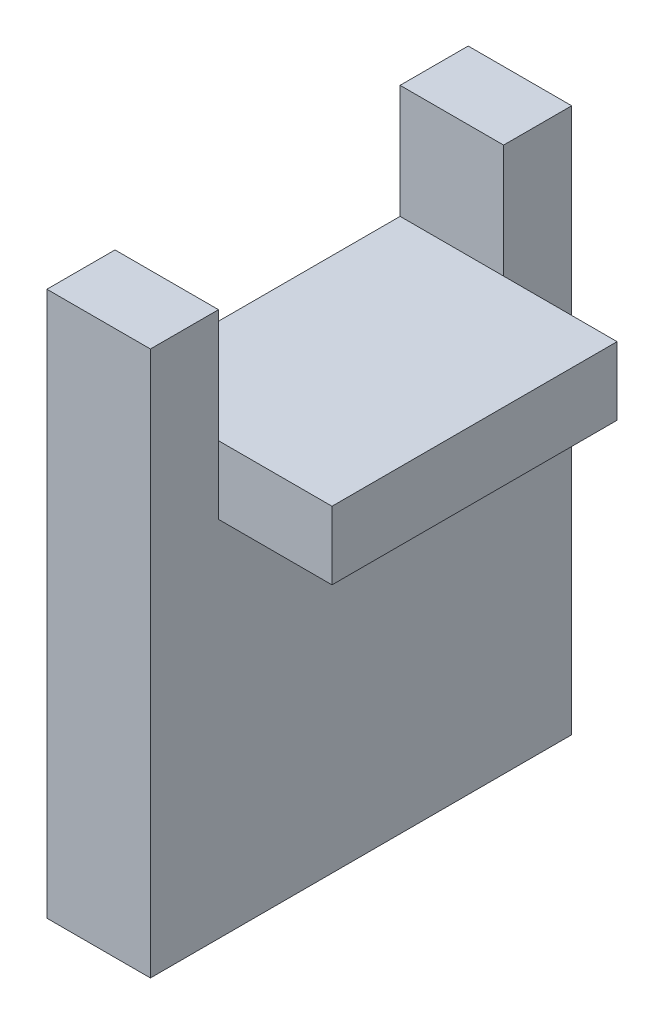
SolidWorks part; units mm, degrees
ref_plane "Front Plane" through (0, 0, 0) normal (0, 0, 1) x (1, 0, 0)
ref_plane "Top Plane" through (0, 0, 0) normal (0, 1, 0) x (1, 0, 0)
ref_plane "Right Plane" through (0, 0, 0) normal (1, 0, 0) x (0, 0, -1)
sketch "Sketch1" plane through (0, 0, 0) normal (0, 1, 0) x (1, 0, 0)
  line L1 (0, 0) -> (4.56, 0)
  line L2 (0, 0) -> (0, 18.56)
  line L3 (0, 18.56) -> (4.56, 18.56)
  line L4 (4.56, 0) -> (4.56, 18.56)
  dimension "D1" = 4.56
  dimension "D2" = 18.56
extrude "Boss-Extrude2" add sketch "Sketch1" along normal blind 24
sketch "Sketch2" plane through (0, 24, 0) normal (0, 1, 0) x (1, 0, 0)
  line L0 (4.56, 0) -> (4.56, 3) construction
  line L1 (4.56, 0) -> (4.56, 18.56) construction
  line L2 (4.56, 18.56) -> (4.56, 15.56) construction
  line L3 (0, 18.56) -> (0, 0) construction
  line L4 (4.56, 3) -> (0, 3)
  line L5 (4.56, 3) -> (4.56, 15.56)
  line L6 (4.56, 15.56) -> (0, 15.56)
  line L7 (0, 3) -> (0, 15.56)
extrude "Cut-Extrude1" cut sketch "Sketch2" against normal blind 5
sketch "Sketch3" plane through (4.56, 0, 0) normal (1, 0, 0) x (0, 0, -1)
  line L1 (3, 19) -> (15.56, 19)
  line L2 (3, 19) -> (3, 16)
  line L3 (3, 16) -> (15.56, 16)
  line L4 (15.56, 19) -> (15.56, 16)
  dimension "D1" = 12.56
  dimension "D2" = 3
extrude "Boss-Extrude3" add sketch "Sketch3" along normal blind 5
